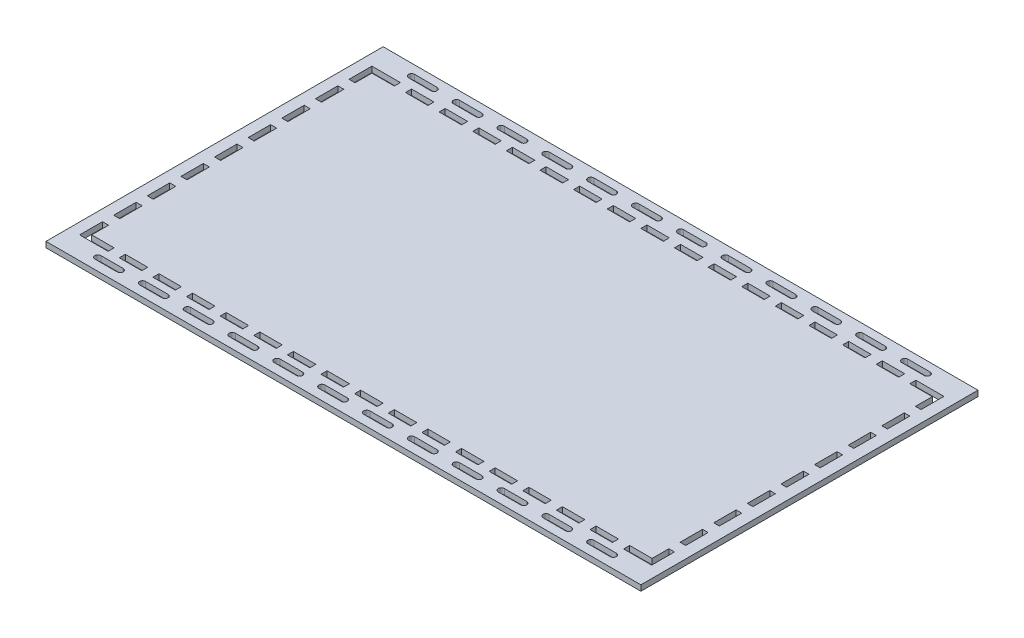
SolidWorks part; units mm, degrees
ref_plane "Front Plane" through (0, 0, 0) normal (0, 0, 1) x (1, 0, 0)
ref_plane "Top Plane" through (0, 0, 0) normal (0, 1, 0) x (1, 0, 0)
ref_plane "Right Plane" through (0, 0, 0) normal (1, 0, 0) x (0, 0, -1)
sketch "Sketch7" plane through (0, 0, 0) normal (0, 1, 0) x (1, 0, 0)
  line L1 (317.5, 158.75) -> (-317.5, 158.75)
  line L2 (317.5, 158.75) -> (317.5, -158.75)
  line L3 (317.5, -158.75) -> (-317.5, -158.75)
  line L4 (-317.5, 158.75) -> (-317.5, -158.75)
  line L5 (0, -158.75) -> (0, 158.75) construction
  line L6 (317.5, 0) -> (-317.5, 0) construction
  line L56 (-317.5, 146.05) -> (-273.875, 146.05) construction
  line L57 (273.875, 146.05) -> (317.5, 146.05) construction
  line L78 (-273.875, 146.05) -> (-317.5, 146.05) construction
  line L82 (-273.875, 146.05) -> (-273.875, 158.75) construction
  dimension "D3" = 317.5
  dimension "D7" = 12.7
  dimension "D9" = 635
extrude "Boss-Extrude4" add sketch "Sketch7" along normal blind 6.35
sketch "Sketch8" plane through (0, 0, 0) normal (0, 1, 0) x (1, 0, 0)
  line L0 (-292.1, 158.75) -> (-292.1, 165.608)
  line L1 (-292.1, 165.608) -> (-279.4, 165.608)
  line L2 (-279.4, 165.608) -> (-279.4, 158.75)
  line L3 (317.5, 158.75) -> (-317.5, 158.75) construction
  line L4 (-292.1, 158.75) -> (-279.4, 158.75)
  line L29 (12.7, 165.608) -> (25.4, 165.608)
  line L58 (-317.5, 139.7) -> (-324.358, 139.7)
  line L59 (-317.5, 158.75) -> (-317.5, -158.75) construction
  line L60 (-324.358, 139.7) -> (-324.358, 127)
  line L61 (-324.358, 127) -> (-317.5, 127)
  line L62 (-317.5, 139.7) -> (-317.5, 127)
  line L63 (-324.358, 88.9) -> (-317.5, 88.9)
  line L64 (-317.5, 101.6) -> (-317.5, 88.9)
  line L65 (-317.5, 101.6) -> (-324.358, 101.6)
  line L66 (-324.358, 101.6) -> (-324.358, 88.9)
  line L67 (-324.358, 50.8) -> (-317.5, 50.8)
  line L68 (-317.5, 63.5) -> (-317.5, 50.8)
  line L69 (-317.5, 63.5) -> (-324.358, 63.5)
  line L70 (-324.358, 63.5) -> (-324.358, 50.8)
  line L71 (-324.358, 12.7) -> (-317.5, 12.7)
  line L72 (-317.5, 25.4) -> (-317.5, 12.7)
  line L73 (-317.5, 25.4) -> (-324.358, 25.4)
  line L74 (-324.358, 25.4) -> (-324.358, 12.7)
  line L75 (-324.358, -25.4) -> (-317.5, -25.4)
  line L76 (-317.5, -12.7) -> (-317.5, -25.4)
  line L77 (-317.5, -12.7) -> (-324.358, -12.7)
  line L78 (-324.358, -12.7) -> (-324.358, -25.4)
  line L95 (-324.358, -63.5) -> (-317.5, -63.5)
  line L120 (-317.5, -50.8) -> (-317.5, -63.5)
  line L121 (-317.5, -50.8) -> (-324.358, -50.8)
  line L122 (-324.358, -50.8) -> (-324.358, -63.5)
  line L123 (-324.358, -101.6) -> (-317.5, -101.6)
  line L124 (-317.5, -88.9) -> (-317.5, -101.6)
  line L125 (-317.5, -88.9) -> (-324.358, -88.9)
  line L126 (-324.358, -88.9) -> (-324.358, -101.6)
  line L127 (-324.358, -139.7) -> (-317.5, -139.7)
  line L128 (-317.5, -127) -> (-317.5, -139.7)
  line L129 (-317.5, -127) -> (-324.358, -127)
  line L130 (-324.358, -127) -> (-324.358, -139.7)
  line L131 (-317.5, -158.75) -> (317.5, -158.75) construction
  line L132 (-254, 165.608) -> (-241.3, 165.608)
  line L133 (-241.3, 165.608) -> (-241.3, 158.75)
  line L134 (-254, 158.75) -> (-241.3, 158.75)
  line L135 (-254, 158.75) -> (-254, 165.608)
  line L136 (-215.9, 165.608) -> (-203.2, 165.608)
  line L137 (-203.2, 165.608) -> (-203.2, 158.75)
  line L138 (-215.9, 158.75) -> (-203.2, 158.75)
  line L139 (-215.9, 158.75) -> (-215.9, 165.608)
  line L140 (-177.8, 165.608) -> (-165.1, 165.608)
  line L141 (-165.1, 165.608) -> (-165.1, 158.75)
  line L142 (-177.8, 158.75) -> (-165.1, 158.75)
  line L143 (-177.8, 158.75) -> (-177.8, 165.608)
  line L144 (-139.7, 165.608) -> (-127, 165.608)
  line L145 (-127, 165.608) -> (-127, 158.75)
  line L146 (-139.7, 158.75) -> (-127, 158.75)
  line L147 (-139.7, 158.75) -> (-139.7, 165.608)
  line L148 (-101.6, 165.608) -> (-88.9, 165.608)
  line L149 (-88.9, 165.608) -> (-88.9, 158.75)
  line L150 (-101.6, 158.75) -> (-88.9, 158.75)
  line L151 (-101.6, 158.75) -> (-101.6, 165.608)
  line L152 (-63.5, 165.608) -> (-50.8, 165.608)
  line L153 (-50.8, 165.608) -> (-50.8, 158.75)
  line L154 (-63.5, 158.75) -> (-50.8, 158.75)
  line L155 (-63.5, 158.75) -> (-63.5, 165.608)
  line L156 (-25.4, 165.608) -> (-12.7, 165.608)
  line L157 (-12.7, 165.608) -> (-12.7, 158.75)
  line L158 (-25.4, 158.75) -> (-12.7, 158.75)
  line L159 (-25.4, 158.75) -> (-25.4, 165.608)
  line L160 (-44.45, 139.7) -> (-51.308, 139.7) [skipped]
  line L161 (-51.308, 139.7) -> (-51.308, 127) [skipped]
  line L162 (-51.308, 127) -> (-44.45, 127) [skipped]
  line L163 (-44.45, 139.7) -> (-44.45, 127) [skipped]
  line L164 (-51.308, 88.9) -> (-44.45, 88.9) [skipped]
  line L165 (-44.45, 101.6) -> (-44.45, 88.9) [skipped]
  line L166 (-44.45, 101.6) -> (-51.308, 101.6) [skipped]
  line L167 (-51.308, 101.6) -> (-51.308, 88.9) [skipped]
  line L168 (-51.308, 50.8) -> (-44.45, 50.8) [skipped]
  line L169 (-44.45, 63.5) -> (-44.45, 50.8) [skipped]
  line L170 (-44.45, 63.5) -> (-51.308, 63.5) [skipped]
  line L171 (-51.308, 63.5) -> (-51.308, 50.8) [skipped]
  line L172 (-51.308, 12.7) -> (-44.45, 12.7) [skipped]
  line L173 (-44.45, 25.4) -> (-44.45, 12.7) [skipped]
  line L174 (-44.45, 25.4) -> (-51.308, 25.4) [skipped]
  line L175 (-51.308, 25.4) -> (-51.308, 12.7) [skipped]
  line L176 (-51.308, -25.4) -> (-44.45, -25.4) [skipped]
  line L177 (-44.45, -12.7) -> (-44.45, -25.4) [skipped]
  line L178 (-44.45, -12.7) -> (-51.308, -12.7) [skipped]
  line L179 (-51.308, -12.7) -> (-51.308, -25.4) [skipped]
  line L180 (25.4, 165.608) -> (25.4, 158.75)
  line L181 (12.7, 158.75) -> (25.4, 158.75)
  line L182 (12.7, 158.75) -> (12.7, 165.608)
  line L183 (50.8, 165.608) -> (63.5, 165.608)
  line L184 (63.5, 165.608) -> (63.5, 158.75)
  line L185 (50.8, 158.75) -> (63.5, 158.75)
  line L186 (50.8, 158.75) -> (50.8, 165.608)
  line L187 (88.9, 165.608) -> (101.6, 165.608)
  line L188 (101.6, 165.608) -> (101.6, 158.75)
  line L189 (88.9, 158.75) -> (101.6, 158.75)
  line L190 (88.9, 158.75) -> (88.9, 165.608)
  line L191 (127, 165.608) -> (139.7, 165.608)
  line L192 (139.7, 165.608) -> (139.7, 158.75)
  line L193 (127, 158.75) -> (139.7, 158.75)
  line L194 (127, 158.75) -> (127, 165.608)
  line L195 (165.1, 165.608) -> (177.8, 165.608)
  line L196 (177.8, 165.608) -> (177.8, 158.75)
  line L197 (165.1, 158.75) -> (177.8, 158.75)
  line L198 (165.1, 158.75) -> (165.1, 165.608)
  line L199 (203.2, 165.608) -> (215.9, 165.608)
  line L200 (215.9, 165.608) -> (215.9, 158.75)
  line L201 (203.2, 158.75) -> (215.9, 158.75)
  line L202 (203.2, 158.75) -> (203.2, 165.608)
  line L203 (241.3, 165.608) -> (254, 165.608)
  line L204 (254, 165.608) -> (254, 158.75)
  line L205 (241.3, 158.75) -> (254, 158.75)
  line L206 (241.3, 158.75) -> (241.3, 165.608)
  line L207 (279.4, 165.608) -> (292.1, 165.608)
  line L208 (292.1, 165.608) -> (292.1, 158.75)
  line L209 (279.4, 158.75) -> (292.1, 158.75)
  line L210 (279.4, 158.75) -> (279.4, 165.608)
  line L211 (317.5, -158.75) -> (317.5, 158.75) construction
  line L212 (-317.5, -158.75) -> (317.5, 158.75) construction
  line L213 (0, 0) -> (317.5, 0) construction
  line L214 (0, 0) -> (0, -158.75) construction
  line L215 (324.358, -127) -> (324.358, -139.7)
  line L216 (317.5, -127) -> (324.358, -127)
  line L217 (317.5, -127) -> (317.5, -139.7)
  line L218 (324.358, -139.7) -> (317.5, -139.7)
  line L219 (324.358, -88.9) -> (324.358, -101.6)
  line L220 (317.5, -88.9) -> (324.358, -88.9)
  line L221 (317.5, -88.9) -> (317.5, -101.6)
  line L222 (324.358, -101.6) -> (317.5, -101.6)
  line L223 (324.358, -50.8) -> (324.358, -63.5)
  line L224 (317.5, -50.8) -> (324.358, -50.8)
  line L225 (317.5, -50.8) -> (317.5, -63.5)
  line L226 (324.358, -63.5) -> (317.5, -63.5)
  line L227 (324.358, -12.7) -> (324.358, -25.4)
  line L228 (317.5, -12.7) -> (324.358, -12.7)
  line L229 (317.5, -12.7) -> (317.5, -25.4)
  line L230 (324.358, -25.4) -> (317.5, -25.4)
  line L231 (324.358, 25.4) -> (324.358, 12.7)
  line L232 (317.5, 25.4) -> (324.358, 25.4)
  line L233 (317.5, 25.4) -> (317.5, 12.7)
  line L234 (324.358, 12.7) -> (317.5, 12.7)
  line L235 (324.358, 63.5) -> (324.358, 50.8)
  line L236 (317.5, 63.5) -> (324.358, 63.5)
  line L237 (317.5, 63.5) -> (317.5, 50.8)
  line L238 (324.358, 50.8) -> (317.5, 50.8)
  line L239 (324.358, 101.6) -> (324.358, 88.9)
  line L240 (317.5, 101.6) -> (324.358, 101.6)
  line L241 (317.5, 101.6) -> (317.5, 88.9)
  line L242 (324.358, 88.9) -> (317.5, 88.9)
  line L243 (317.5, 139.7) -> (317.5, 127)
  line L244 (324.358, 127) -> (317.5, 127)
  line L245 (324.358, 139.7) -> (324.358, 127)
  line L246 (317.5, 139.7) -> (324.358, 139.7)
  line L247 (279.4, -158.75) -> (279.4, -165.608)
  line L248 (279.4, -158.75) -> (292.1, -158.75)
  line L249 (292.1, -165.608) -> (292.1, -158.75)
  line L250 (279.4, -165.608) -> (292.1, -165.608)
  line L251 (241.3, -158.75) -> (241.3, -165.608)
  line L252 (241.3, -158.75) -> (254, -158.75)
  line L253 (254, -165.608) -> (254, -158.75)
  line L254 (241.3, -165.608) -> (254, -165.608)
  line L255 (203.2, -158.75) -> (203.2, -165.608)
  line L256 (203.2, -158.75) -> (215.9, -158.75)
  line L257 (215.9, -165.608) -> (215.9, -158.75)
  line L258 (203.2, -165.608) -> (215.9, -165.608)
  line L259 (165.1, -158.75) -> (165.1, -165.608)
  line L260 (165.1, -158.75) -> (177.8, -158.75)
  line L261 (177.8, -165.608) -> (177.8, -158.75)
  line L262 (165.1, -165.608) -> (177.8, -165.608)
  line L263 (127, -158.75) -> (127, -165.608)
  line L264 (127, -158.75) -> (139.7, -158.75)
  line L265 (139.7, -165.608) -> (139.7, -158.75)
  line L266 (127, -165.608) -> (139.7, -165.608)
  line L267 (88.9, -158.75) -> (88.9, -165.608)
  line L268 (88.9, -158.75) -> (101.6, -158.75)
  line L269 (101.6, -165.608) -> (101.6, -158.75)
  line L270 (88.9, -165.608) -> (101.6, -165.608)
  line L271 (50.8, -158.75) -> (50.8, -165.608)
  line L272 (50.8, -158.75) -> (63.5, -158.75)
  line L273 (63.5, -165.608) -> (63.5, -158.75)
  line L274 (50.8, -165.608) -> (63.5, -165.608)
  line L275 (12.7, -158.75) -> (12.7, -165.608)
  line L276 (12.7, -158.75) -> (25.4, -158.75)
  line L277 (25.4, -165.608) -> (25.4, -158.75)
  line L278 (-25.4, -158.75) -> (-25.4, -165.608)
  line L279 (-25.4, -158.75) -> (-12.7, -158.75)
  line L280 (-12.7, -165.608) -> (-12.7, -158.75)
  line L281 (-25.4, -165.608) -> (-12.7, -165.608)
  line L282 (-63.5, -158.75) -> (-63.5, -165.608)
  line L283 (-63.5, -158.75) -> (-50.8, -158.75)
  line L284 (-50.8, -165.608) -> (-50.8, -158.75)
  line L285 (-63.5, -165.608) -> (-50.8, -165.608)
  line L286 (-101.6, -158.75) -> (-101.6, -165.608)
  line L287 (-101.6, -158.75) -> (-88.9, -158.75)
  line L288 (-88.9, -165.608) -> (-88.9, -158.75)
  line L289 (-101.6, -165.608) -> (-88.9, -165.608)
  line L290 (-139.7, -158.75) -> (-139.7, -165.608)
  line L291 (-139.7, -158.75) -> (-127, -158.75)
  line L292 (-127, -165.608) -> (-127, -158.75)
  line L293 (-139.7, -165.608) -> (-127, -165.608)
  line L294 (-177.8, -158.75) -> (-177.8, -165.608)
  line L295 (-177.8, -158.75) -> (-165.1, -158.75)
  line L296 (-165.1, -165.608) -> (-165.1, -158.75)
  line L297 (-177.8, -165.608) -> (-165.1, -165.608)
  line L298 (-215.9, -158.75) -> (-215.9, -165.608)
  line L299 (-215.9, -158.75) -> (-203.2, -158.75)
  line L300 (-203.2, -165.608) -> (-203.2, -158.75)
  line L301 (-215.9, -165.608) -> (-203.2, -165.608)
  line L302 (-254, -158.75) -> (-254, -165.608)
  line L303 (-254, -158.75) -> (-241.3, -158.75)
  line L304 (-241.3, -165.608) -> (-241.3, -158.75)
  line L305 (-254, -165.608) -> (-241.3, -165.608)
  line L306 (12.7, -165.608) -> (25.4, -165.608)
  line L307 (-292.1, -158.75) -> (-279.4, -158.75)
  line L308 (-279.4, -165.608) -> (-279.4, -158.75)
  line L309 (-292.1, -165.608) -> (-279.4, -165.608)
  line L310 (-292.1, -158.75) -> (-292.1, -165.608)
  dimension "D1" = 12.7
  dimension "D2" = 6.858
  dimension "D3" = 25.4
  dimension "D4" = 16
  dimension "D5" = 25.4
  dimension "D6" = 25.4
  dimension "D8" = 19.05
  dimension "D12" = 19.05
  dimension "D13" = 25.4
  dimension "D9" = 8
extrude "Boss-Extrude5" add sketch "Sketch8" along normal blind 6.35
sketch "Sketch10" plane through (0, 6.35, 0) normal (0, 1, 0) x (1, 0, 0)
  line L0 (279.4, -165.608) -> (292.1, -165.608) construction
  line L1 (-324.358, 165.608) -> (323.85, 165.608)
  line L3 (-324.358, -165.608) -> (323.85, -165.608)
  line L5 (-324.358, 139.7) -> (-324.358, 127) construction
  line L6 (292.1, 165.608) -> (279.4, 165.608) construction
  line L8 (-292.1, 178.308) -> (-266.7, 178.308) construction
  line L9 (-308.0562, 191.008) -> (323.85, 191.008)
  line L11 (-324.358, -191.008) -> (324.358, -191.008)
  line L13 (-292.1, 181.737) -> (-266.7, 181.737)
  line L14 (-292.1, 174.879) -> (-266.7, 174.879)
  line L15 (-241.3, 178.308) -> (-215.9, 178.308) construction
  line L16 (-241.3, 181.737) -> (-215.9, 181.737)
  line L17 (-241.3, 174.879) -> (-215.9, 174.879)
  line L18 (-190.5, 178.308) -> (-165.1, 178.308) construction
  line L19 (-190.5, 181.737) -> (-165.1, 181.737)
  line L20 (-190.5, 174.879) -> (-165.1, 174.879)
  line L21 (-139.7, 178.308) -> (-114.3, 178.308) construction
  line L22 (-139.7, 181.737) -> (-114.3, 181.737)
  line L23 (-139.7, 174.879) -> (-114.3, 174.879)
  line L24 (-88.9, 178.308) -> (-63.5, 178.308) construction
  line L25 (-88.9, 181.737) -> (-63.5, 181.737)
  line L26 (-88.9, 174.879) -> (-63.5, 174.879)
  line L27 (-38.1, 178.308) -> (-12.7, 178.308) construction
  line L28 (-38.1, 181.737) -> (-12.7, 181.737)
  line L29 (-38.1, 174.879) -> (-12.7, 174.879)
  line L30 (12.7, 178.308) -> (38.1, 178.308) construction
  line L31 (12.7, 181.737) -> (38.1, 181.737)
  line L32 (12.7, 174.879) -> (38.1, 174.879)
  line L33 (63.5, 178.308) -> (88.9, 178.308) construction
  line L34 (63.5, 181.737) -> (88.9, 181.737)
  line L35 (63.5, 174.879) -> (88.9, 174.879)
  line L36 (114.3, 178.308) -> (139.7, 178.308) construction
  line L37 (114.3, 181.737) -> (139.7, 181.737)
  line L38 (114.3, 174.879) -> (139.7, 174.879)
  line L39 (165.1, 178.308) -> (190.5, 178.308) construction
  line L40 (165.1, 181.737) -> (190.5, 181.737)
  line L41 (165.1, 174.879) -> (190.5, 174.879)
  line L42 (215.9, 178.308) -> (241.3, 178.308) construction
  line L43 (215.9, 181.737) -> (241.3, 181.737)
  line L44 (215.9, 174.879) -> (241.3, 174.879)
  line L45 (266.7, 178.308) -> (292.1, 178.308) construction
  line L46 (266.7, 181.737) -> (292.1, 181.737)
  line L47 (266.7, 174.879) -> (292.1, 174.879)
  line L48 (-308.0562, 191.008) -> (-337.058, 191.008)
  line L51 (-241.3, -177.292) -> (-215.9, -177.292) construction
  line L52 (-241.3, -173.863) -> (-215.9, -173.863)
  line L53 (-241.3, -180.721) -> (-215.9, -180.721)
  line L54 (-190.5, -177.292) -> (-165.1, -177.292) construction
  line L55 (-190.5, -173.863) -> (-165.1, -173.863)
  line L56 (-190.5, -180.721) -> (-165.1, -180.721)
  line L57 (-139.7, -177.292) -> (-114.3, -177.292) construction
  line L58 (-139.7, -173.863) -> (-114.3, -173.863)
  line L59 (-139.7, -180.721) -> (-114.3, -180.721)
  line L60 (-88.9, -177.292) -> (-63.5, -177.292) construction
  line L61 (-88.9, -173.863) -> (-63.5, -173.863)
  line L62 (-88.9, -180.721) -> (-63.5, -180.721)
  line L63 (-38.1, -177.292) -> (-12.7, -177.292) construction
  line L64 (-38.1, -173.863) -> (-12.7, -173.863)
  line L65 (-38.1, -180.721) -> (-12.7, -180.721)
  line L66 (12.7, -177.292) -> (38.1, -177.292) construction
  line L67 (12.7, -173.863) -> (38.1, -173.863)
  line L68 (12.7, -180.721) -> (38.1, -180.721)
  line L69 (63.5, -177.292) -> (88.9, -177.292) construction
  line L70 (63.5, -173.863) -> (88.9, -173.863)
  line L71 (63.5, -180.721) -> (88.9, -180.721)
  line L72 (114.3, -177.292) -> (139.7, -177.292) construction
  line L73 (114.3, -173.863) -> (139.7, -173.863)
  line L74 (114.3, -180.721) -> (139.7, -180.721)
  line L75 (165.1, -177.292) -> (190.5, -177.292) construction
  line L76 (165.1, -173.863) -> (190.5, -173.863)
  line L77 (165.1, -180.721) -> (190.5, -180.721)
  line L78 (215.9, -177.292) -> (241.3, -177.292) construction
  line L79 (215.9, -173.863) -> (241.3, -173.863)
  line L80 (215.9, -180.721) -> (241.3, -180.721)
  line L81 (266.7, -177.292) -> (292.1, -177.292) construction
  line L82 (266.7, -173.863) -> (292.1, -173.863)
  line L83 (266.7, -180.721) -> (292.1, -180.721)
  line L84 (-324.358, 165.608) -> (-324.358, -165.608)
  line L87 (-292.1, -177.292) -> (-266.7, -177.292) construction
  line L88 (-292.1, -173.863) -> (-266.7, -173.863)
  line L89 (-292.1, -180.721) -> (-266.7, -180.721)
  line L92 (-324.358, -191.008) -> (-337.058, -191.008)
  line L93 (-337.058, 191.008) -> (-337.058, -191.008)
  line L94 (324.358, -191.008) -> (337.058, -191.008)
  line L95 (323.85, -165.608) -> (323.85, 165.608)
  line L96 (323.85, 191.008) -> (337.058, 191.008)
  line L97 (337.058, -191.008) -> (337.058, 191.008)
  arc A0 (-292.1, 181.737) -> (-292.1, 174.879) centre (-292.1, 178.308) ccw
  arc A1 (-266.7, 174.879) -> (-266.7, 181.737) centre (-266.7, 178.308) ccw
  arc A2 (-241.3, 181.737) -> (-241.3, 174.879) centre (-241.3, 178.308) ccw
  arc A3 (-215.9, 174.879) -> (-215.9, 181.737) centre (-215.9, 178.308) ccw
  arc A4 (-190.5, 181.737) -> (-190.5, 174.879) centre (-190.5, 178.308) ccw
  arc A5 (-165.1, 174.879) -> (-165.1, 181.737) centre (-165.1, 178.308) ccw
  arc A6 (-139.7, 181.737) -> (-139.7, 174.879) centre (-139.7, 178.308) ccw
  arc A7 (-114.3, 174.879) -> (-114.3, 181.737) centre (-114.3, 178.308) ccw
  arc A8 (-88.9, 181.737) -> (-88.9, 174.879) centre (-88.9, 178.308) ccw
  arc A9 (-63.5, 174.879) -> (-63.5, 181.737) centre (-63.5, 178.308) ccw
  arc A10 (-38.1, 181.737) -> (-38.1, 174.879) centre (-38.1, 178.308) ccw
  arc A11 (-12.7, 174.879) -> (-12.7, 181.737) centre (-12.7, 178.308) ccw
  arc A12 (12.7, 181.737) -> (12.7, 174.879) centre (12.7, 178.308) ccw
  arc A13 (38.1, 174.879) -> (38.1, 181.737) centre (38.1, 178.308) ccw
  arc A14 (63.5, 181.737) -> (63.5, 174.879) centre (63.5, 178.308) ccw
  arc A15 (88.9, 174.879) -> (88.9, 181.737) centre (88.9, 178.308) ccw
  arc A16 (114.3, 181.737) -> (114.3, 174.879) centre (114.3, 178.308) ccw
  arc A17 (139.7, 174.879) -> (139.7, 181.737) centre (139.7, 178.308) ccw
  arc A18 (165.1, 181.737) -> (165.1, 174.879) centre (165.1, 178.308) ccw
  arc A19 (190.5, 174.879) -> (190.5, 181.737) centre (190.5, 178.308) ccw
  arc A20 (215.9, 181.737) -> (215.9, 174.879) centre (215.9, 178.308) ccw
  arc A21 (241.3, 174.879) -> (241.3, 181.737) centre (241.3, 178.308) ccw
  arc A22 (266.7, 181.737) -> (266.7, 174.879) centre (266.7, 178.308) ccw
  arc A23 (292.1, 174.879) -> (292.1, 181.737) centre (292.1, 178.308) ccw
  arc A26 (-241.3, -173.863) -> (-241.3, -180.721) centre (-241.3, -177.292) ccw
  arc A27 (-215.9, -180.721) -> (-215.9, -173.863) centre (-215.9, -177.292) ccw
  arc A28 (-190.5, -173.863) -> (-190.5, -180.721) centre (-190.5, -177.292) ccw
  arc A29 (-165.1, -180.721) -> (-165.1, -173.863) centre (-165.1, -177.292) ccw
  arc A30 (-139.7, -173.863) -> (-139.7, -180.721) centre (-139.7, -177.292) ccw
  arc A31 (-114.3, -180.721) -> (-114.3, -173.863) centre (-114.3, -177.292) ccw
  arc A32 (-88.9, -173.863) -> (-88.9, -180.721) centre (-88.9, -177.292) ccw
  arc A33 (-63.5, -180.721) -> (-63.5, -173.863) centre (-63.5, -177.292) ccw
  arc A34 (-38.1, -173.863) -> (-38.1, -180.721) centre (-38.1, -177.292) ccw
  arc A35 (-12.7, -180.721) -> (-12.7, -173.863) centre (-12.7, -177.292) ccw
  arc A36 (12.7, -173.863) -> (12.7, -180.721) centre (12.7, -177.292) ccw
  arc A37 (38.1, -180.721) -> (38.1, -173.863) centre (38.1, -177.292) ccw
  arc A38 (63.5, -173.863) -> (63.5, -180.721) centre (63.5, -177.292) ccw
  arc A39 (88.9, -180.721) -> (88.9, -173.863) centre (88.9, -177.292) ccw
  arc A40 (114.3, -173.863) -> (114.3, -180.721) centre (114.3, -177.292) ccw
  arc A41 (139.7, -180.721) -> (139.7, -173.863) centre (139.7, -177.292) ccw
  arc A42 (165.1, -173.863) -> (165.1, -180.721) centre (165.1, -177.292) ccw
  arc A43 (190.5, -180.721) -> (190.5, -173.863) centre (190.5, -177.292) ccw
  arc A44 (215.9, -173.863) -> (215.9, -180.721) centre (215.9, -177.292) ccw
  arc A45 (241.3, -180.721) -> (241.3, -173.863) centre (241.3, -177.292) ccw
  arc A46 (266.7, -173.863) -> (266.7, -180.721) centre (266.7, -177.292) ccw
  arc A47 (292.1, -180.721) -> (292.1, -173.863) centre (292.1, -177.292) ccw
  arc A50 (-292.1, -173.863) -> (-292.1, -180.721) centre (-292.1, -177.292) ccw
  arc A51 (-266.7, -180.721) -> (-266.7, -173.863) centre (-266.7, -177.292) ccw
  point P18 (-279.4, 178.308)
  point P27 (-228.6, 178.308)
  point P34 (-177.8, 178.308)
  point P41 (-127, 178.308)
  point P48 (-76.2, 178.308)
  point P55 (-25.4, 178.308)
  point P62 (25.4, 178.308)
  point P69 (76.2, 178.308)
  point P76 (127, 178.308)
  point P83 (177.8, 178.308)
  point P90 (228.6, 178.308)
  point P97 (279.4, 178.308)
  point P111 (-228.6, -177.292)
  point P118 (-177.8, -177.292)
  point P125 (-127, -177.292)
  point P132 (-76.2, -177.292)
  point P139 (-25.4, -177.292)
  point P146 (25.4, -177.292)
  point P153 (76.2, -177.292)
  point P160 (127, -177.292)
  point P167 (177.8, -177.292)
  point P174 (228.6, -177.292)
  point P181 (279.4, -177.292)
  point P195 (-279.4, -177.292)
  dimension "D1" = 6.858
  dimension "D2" = 12.7
  dimension "D3" = 25.4
  dimension "D4" = 12.7
  dimension "D6" = 50.8
  dimension "D7" = 355.6
  dimension "D8" = 25.4
  dimension "D9" = 25.4
  dimension "D10" = 12.7
  dimension "D11" = 12.7
  dimension "D12" = 12.7
  dimension "D5" = 12
  dimension "D13" = 2
extrude "Boss-Extrude7" add sketch "Sketch10" against normal blind 6.35
